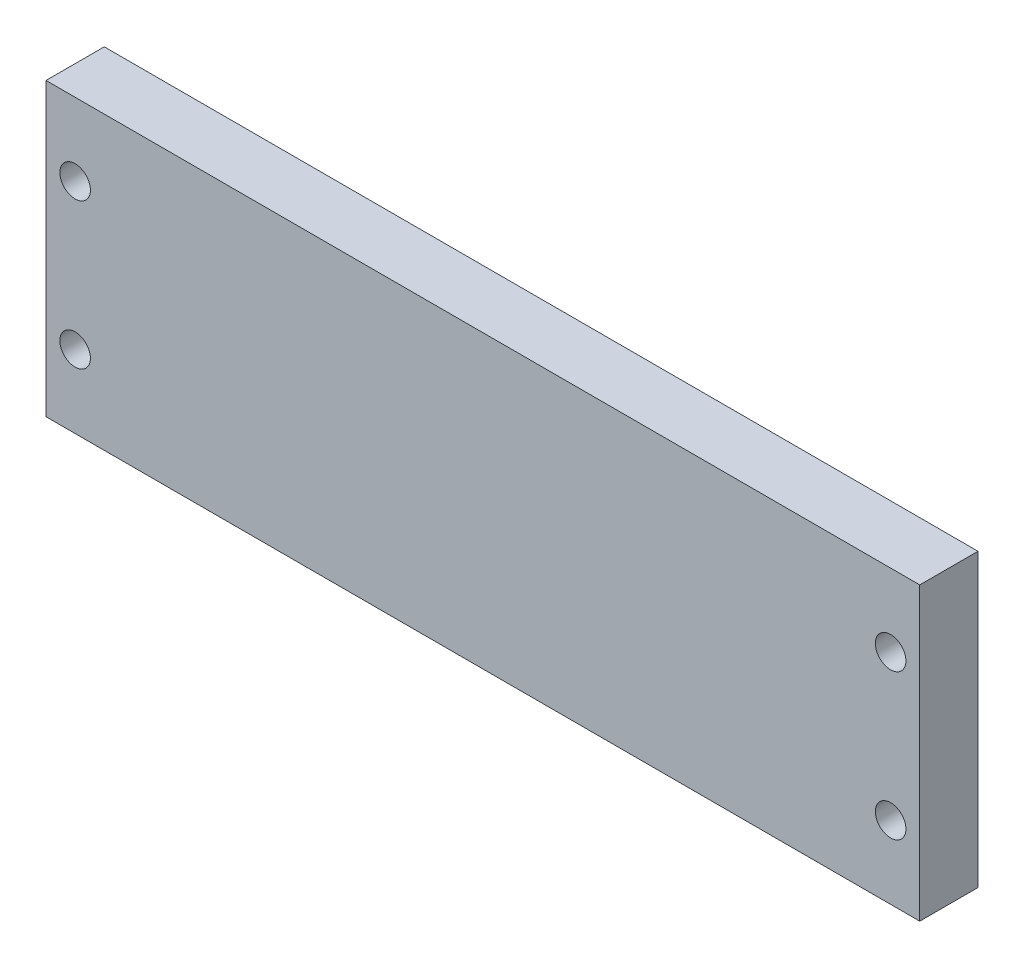
SolidWorks part; units mm, degrees
material "6061 Сплав"
ref_plane "Front" through (0, 0, 0) normal (0, 0, 1) x (1, 0, 0)
ref_plane "Top" through (0, 0, 0) normal (0, 1, 0) x (1, 0, 0)
ref_plane "Right" through (0, 0, 0) normal (1, 0, 0) x (0, 0, -1)
sketch "Эскиз1" plane through (0, 0, 0) normal (0, 0, 1) x (1, 0, 0)
  line L1 (-60, 20) -> (60, 20)
  line L2 (-60, 20) -> (-60, -20)
  line L3 (-60, -20) -> (60, -20)
  line L4 (60, 20) -> (60, -20)
  line L5 (-60, 20) -> (60, -20) construction
  line L6 (-60, -20) -> (60, 20) construction
  point P0 (0, 0)
  dimension "D1" = 120
  dimension "D2" = 40
extrude "Бобышка-Вытянуть1" add sketch "Эскиз1" along normal blind 8
sketch "Эскиз2" plane through (0, 0, 8) normal (0, 0, 1) x (1, 0, 0)
  line L0 (60, 20) -> (-60, 20) construction
  line L1 (-60, 20) -> (-60, -20) construction
  line L2 (-60, -20) -> (60, -20) construction
  circle A0 centre (-56, 10) radius 2.1
  circle A1 centre (-56, -10) radius 2.1
  dimension "D1" = 10
  dimension "D2" = 4
  dimension "D3" = 4
  dimension "D4" = 10
extrude "Вырез-Вытянуть1" cut sketch "Эскиз2" against normal blind 50
pattern_linear "Линейный массив2" count 2 spacing 112 along (1, 0, 0) of "Вырез-Вытянуть1"
sketch "Эскиз3" plane through (0, 0, 0) normal (0, 0, -1) x (-1, 0, 0)
  circle A0 centre (-56, 10) radius 3.55
  circle A1 centre (-56, -10) radius 3.55
  circle A2 centre (56, 10) radius 3.55
  circle A3 centre (56, -10) radius 3.55
extrude "Вырез-Вытянуть2" cut sketch "Эскиз3" against normal blind 5
